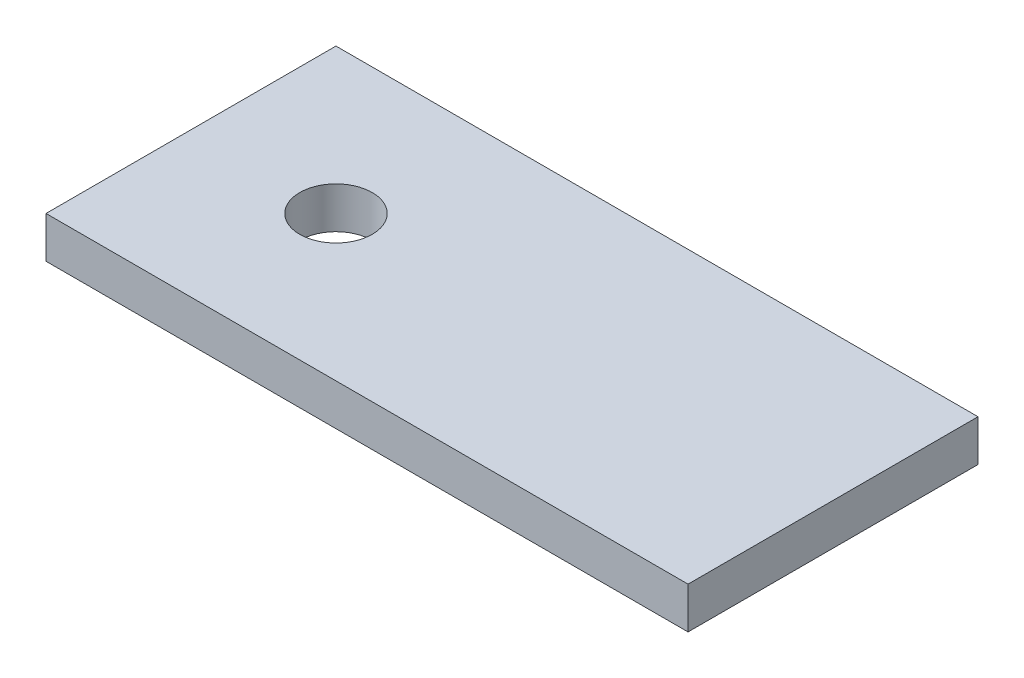
SolidWorks part; units mm, degrees
ref_plane "Alzado" through (0, 0, 0) normal (0, 0, 1) x (1, 0, 0)
ref_plane "Planta" through (0, 0, 0) normal (0, 1, 0) x (1, 0, 0)
ref_plane "Vista lateral" through (0, 0, 0) normal (1, 0, 0) x (0, 0, -1)
sketch "Croquis1" plane through (0, 0, 0) normal (0, 1, 0) x (1, 0, 0)
  line L0 (-31, -7) -> (-24, -7) construction
  line L1 (0, 0) -> (-31, 0)
  line L2 (0, 0) -> (0, -14)
  line L3 (0, -14) -> (-31, -14)
  line L4 (-31, 0) -> (-31, -14)
  circle A0 centre (-24, -7) radius 1.75
  dimension "D4" = 3.5
  dimension "D1" = 14
  dimension "D2" = 31
  dimension "D3" = 7
extrude "Saliente-Extruir1" add sketch "Croquis1" along normal blind 2
